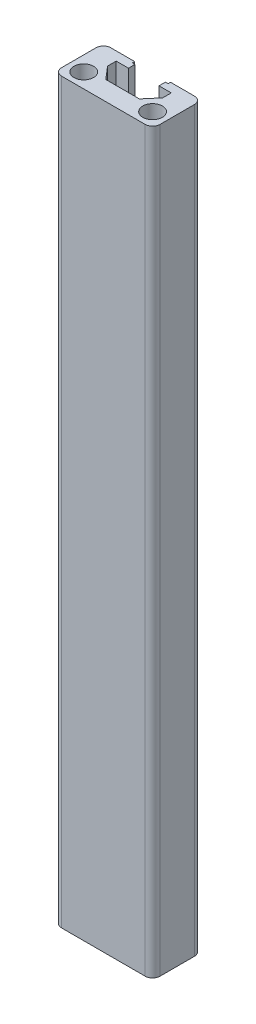
SolidWorks part; units mm, degrees
ref_plane "前视基准面" through (0, 0, 0) normal (0, 0, 1) x (1, 0, 0)
ref_plane "上视基准面" through (0, 0, 0) normal (0, 1, 0) x (1, 0, 0)
ref_plane "右视基准面" through (0, 0, 0) normal (1, 0, 0) x (0, 0, -1)
sketch "草图1" plane through (0, 0, 0) normal (0, 1, 0) x (1, 0, 0)
  line L0 (0, 0) -> (20, 0)
  line L1 (20, 0) -> (20, 10)
  line L2 (20, 10) -> (13.65, 10)
  line L3 (0, 10) -> (0, 0)
  line L4 (6.35, 10) -> (6.35, 9.5104)
  line L5 (6.35, 9.5104) -> (6.9, 9.5104)
  line L6 (6.9, 9.5104) -> (6.9, 8.2)
  line L7 (6.9, 8.2) -> (4.4, 8.2)
  line L8 (4.4, 8.2) -> (4.4, 6.4475)
  line L9 (4.4, 6.4475) -> (6.5873, 3.9)
  line L11 (15.6, 6.4475) -> (15.6, 8.2)
  line L12 (15.6, 8.2) -> (13.1, 8.2)
  line L13 (13.1, 8.2) -> (13.1, 9.5104)
  line L14 (13.1, 9.5104) -> (13.65, 9.5104)
  line L15 (13.65, 9.5104) -> (13.65, 10)
  line L16 (6.35, 10) -> (0, 10)
  line L17 (10, 0) -> (10, 13.7687) construction
  line L18 (6.5873, 3.9) -> (13.4127, 3.9)
  line L19 (13.4127, 3.9) -> (15.6, 6.4475)
  circle A0 centre (3, 3) radius 2
  circle A1 centre (17, 3) radius 2
  point P12 (10, 3.9)
  dimension "D8" = 4
  dimension "D1" = 20
  dimension "D2" = 10
  dimension "D3" = 7.3
  dimension "D4" = 6.2
  dimension "D5" = 1.8
  dimension "D6" = 4.3
  dimension "D7" = 11.2
  dimension "D9" = 3
  dimension "D10" = 14
extrude "凸台-拉伸1" add sketch "草图1" along normal blind 150
fillet "圆角1" radius 1.5 4 edges at (0, 75, -10) (0, 75, 0) (20, 75, -10) (20, 75, 0)
